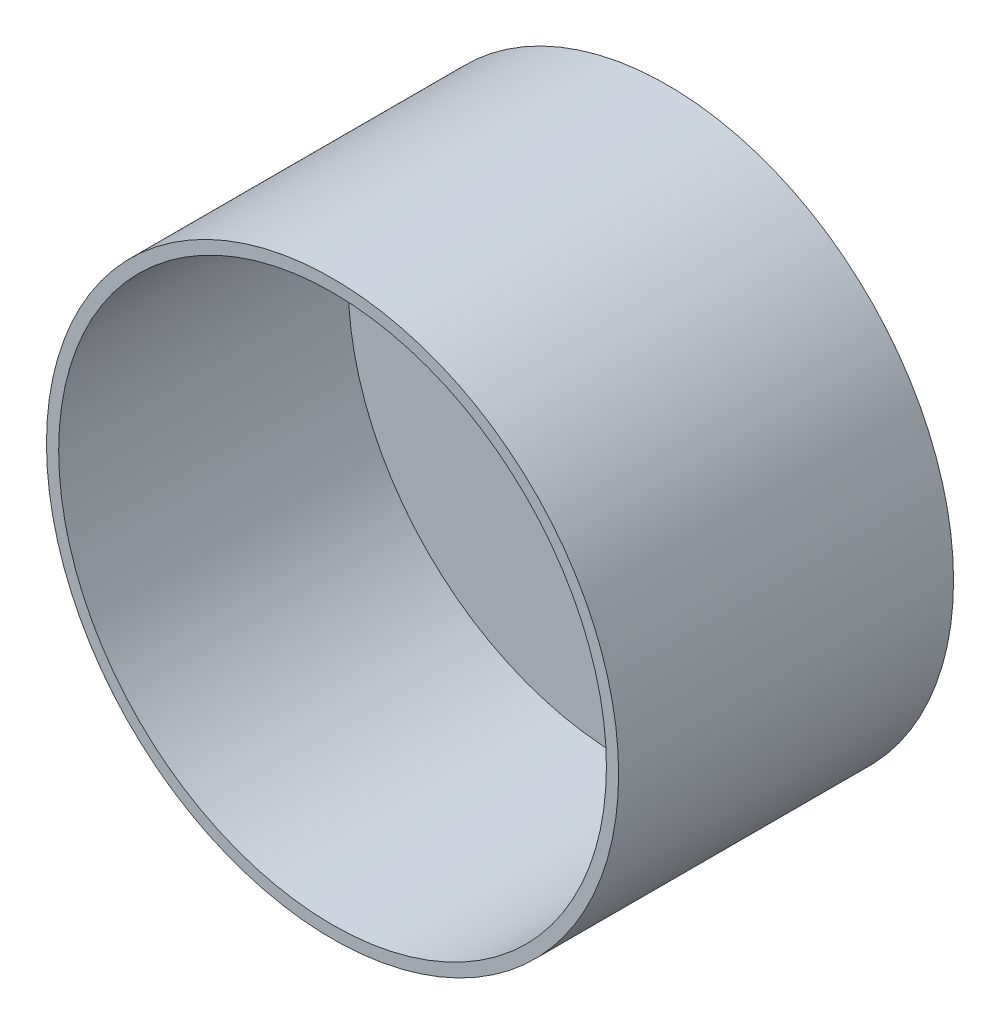
SolidWorks part; units mm, degrees
ref_plane "前视基准面" through (0, 0, 0) normal (0, 0, 1) x (1, 0, 0)
ref_plane "上视基准面" through (0, 0, 0) normal (0, 1, 0) x (1, 0, 0)
ref_plane "右视基准面" through (0, 0, 0) normal (1, 0, 0) x (0, 0, -1)
other "Configuration Table"
sketch "草图1" plane through (0, 0, 0) normal (0, 0, 1) x (1, 0, 0)
  circle A0 centre (0, 0) radius 41
  dimension "D1" = 82
extrude "凸台-拉伸1" add sketch "草图1" along normal blind 48
sketch "草图2" plane through (0, 0, 48) normal (0, 0, 1) x (1, 0, 0)
  circle A0 centre (0, 0) radius 39.25
  dimension "D1" = 78.5
extrude "切除-拉伸1" cut sketch "草图2" against normal blind 41.5
